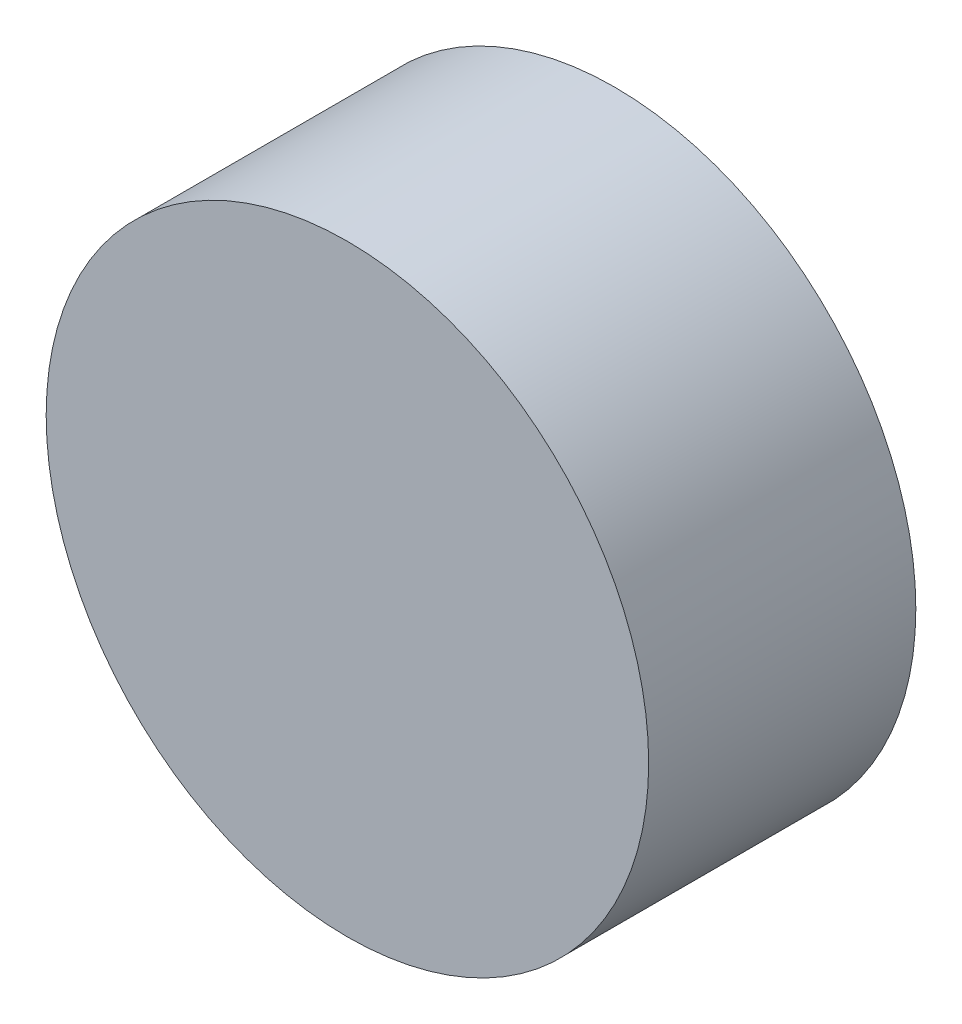
SolidWorks part; units mm, degrees
ref_plane "前视基准面" through (0, 0, 0) normal (0, 0, 1) x (1, 0, 0)
ref_plane "上视基准面" through (0, 0, 0) normal (0, 1, 0) x (1, 0, 0)
ref_plane "右视基准面" through (0, 0, 0) normal (1, 0, 0) x (0, 0, -1)
other "Configuration Table"
sketch "草图1" plane through (0, 0, 0) normal (0, 0, 1) x (1, 0, 0)
  circle A2 centre (0, 0) radius 21.4251
extrude "凸台-拉伸1" add sketch "草图1" along normal blind 19
sketch "草图2" plane through (0, 0, 19) normal (0, 0, 1) x (1, 0, 0)
  line L0 (-55.9495, 24.6791) -> (-58.7243, 4.416)
  line L1 (-60.9032, 25.3575) -> (-63.6781, 5.0944)
  circle A0 centre (0, 0) radius 26.4251
  circle A2 centre (0, 0) radius 16.4251
  circle A3 centre (0, 0) radius 21.4251
  circle A4 centre (0, 0) radius 21.4251
  dimension "D1" = 0
  dimension "D2" = 5
  dimension "D3" = 5
  dimension "D4" = 5
